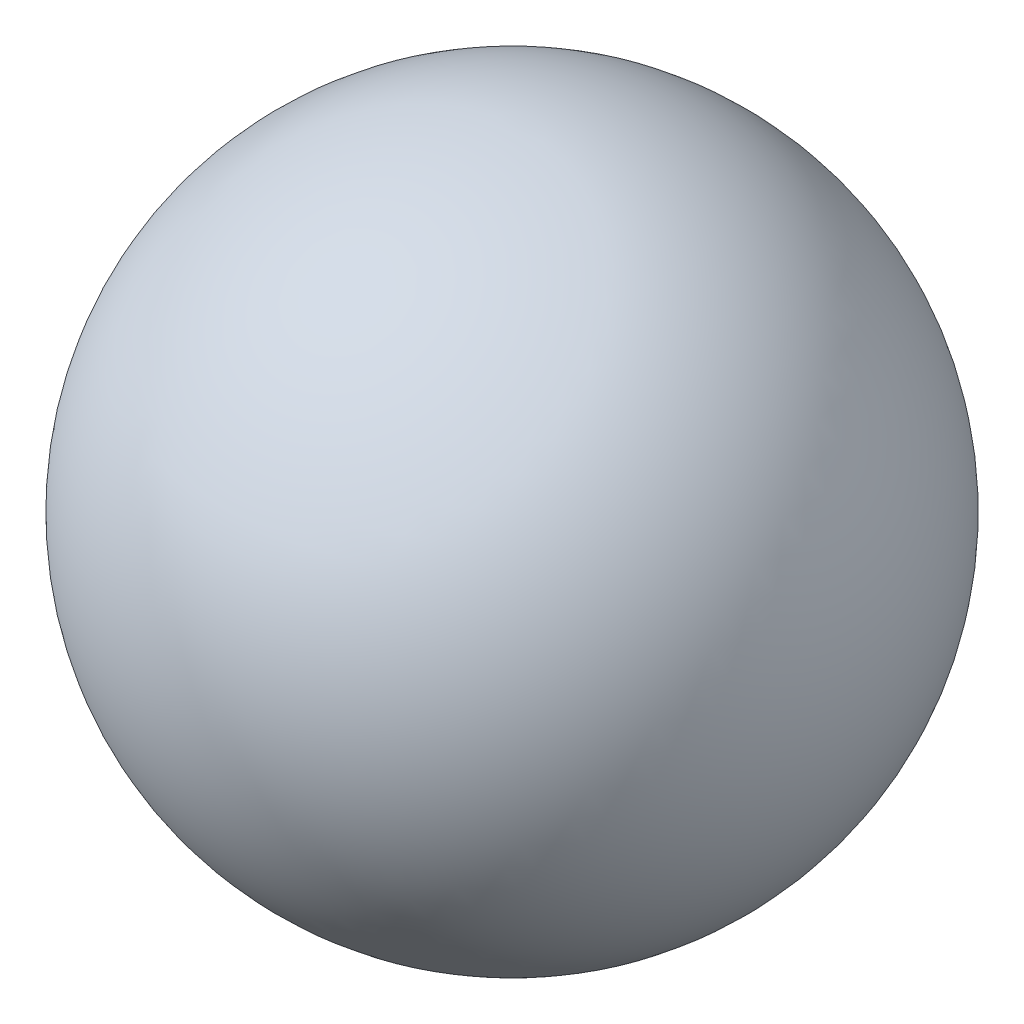
SolidWorks part; units mm, degrees
ref_plane "Front Plane" through (0, 0, 0) normal (0, 0, 1) x (1, 0, 0)
ref_plane "Top Plane" through (0, 0, 0) normal (0, 1, 0) x (1, 0, 0)
ref_plane "Right Plane" through (0, 0, 0) normal (1, 0, 0) x (0, 0, -1)
sketch "Sketch1" plane through (0, 0, 0) normal (0, 0, 1) x (1, 0, 0)
  line L0 (0, 21) -> (0, -21)
  arc A0 (0, 21) -> (0, -21) centre (0, 0) cw
  dimension "D1" = 42
revolve "Revolve1" add sketch "Sketch1" angle 360 about L0
ref_plane "Plane1" through (0, 0, 6) normal (0, 0, 1) x (1, 0, 0)
